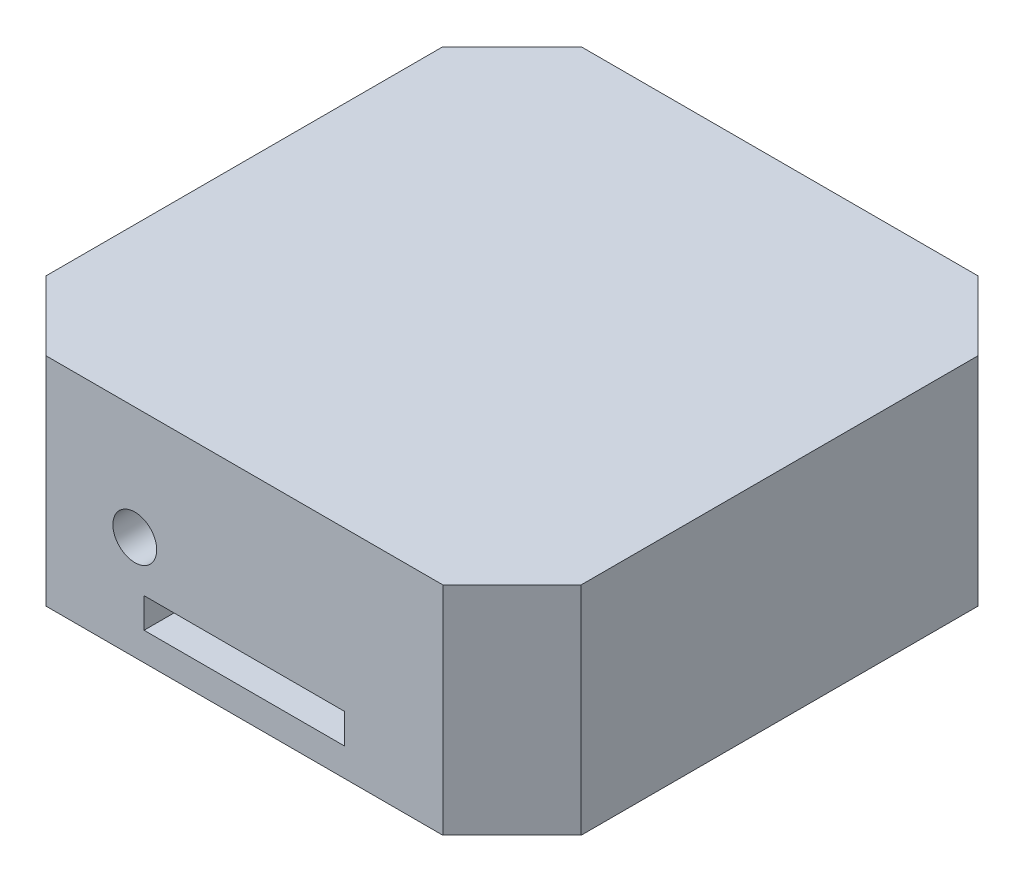
SolidWorks part; units mm, degrees
ref_plane "Ebene vorne" through (0, 0, 0) normal (0, 0, 1) x (1, 0, 0)
ref_plane "Ebene oben" through (0, 0, 0) normal (0, 1, 0) x (1, 0, 0)
ref_plane "Ebene rechts" through (0, 0, 0) normal (1, 0, 0) x (0, 0, -1)
sketch "Sketch2" plane through (0, 0, 0) normal (0, 1, 0) x (1, 0, 0)
  line L8 (-43, 58) -> (43, 58)
  line L9 (43, 58) -> (58, 43)
  line L10 (58, 43) -> (58, -43)
  line L11 (58, -43) -> (43, -58)
  line L12 (43, -58) -> (-43, -58)
  line L13 (-43, -58) -> (-58, -43)
  line L14 (-58, -43) -> (-58, 43)
  line L15 (-58, 43) -> (-43, 58)
  point P2 (-39.0093, 58)
  dimension "D1" = 116
  dimension "D2" = 116
  dimension "D3" = 58
  dimension "D4" = 58
  dimension "D5" = 86
  dimension "D6" = 0
extrude "Boss-Extrude1" add sketch "Sketch2" along normal blind 47
sketch "Sketch3" plane through (0, 0, 58) normal (0, 0, 1) x (1, 0, 0)
  line L0 (-43, 0) -> (43, 0) construction
  line L1 (-21.75, 12.6) -> (21.75, 12.6)
  line L2 (-21.75, 12.6) -> (-21.75, 6.1)
  line L3 (-21.75, 6.1) -> (21.75, 6.1)
  line L4 (21.75, 12.6) -> (21.75, 6.1)
  line L5 (0, 6.1) -> (0, 12.6) construction
  line L6 (-21.75, 9.35) -> (21.75, 9.35) construction
  circle A0 centre (-23.75, 22.55) radius 4.75
  point P0 (0, 9.35)
  point P8 (0, 0)
  dimension "D1" = 9.5
  dimension "D2" = 43.5
  dimension "D3" = 6.5
  dimension "D4" = 6.1
  dimension "D5" = 0
  dimension "D6" = 2
  dimension "D7" = 22.55
extrude "Cut-Extrude1" cut sketch "Sketch3" against normal blind 10
